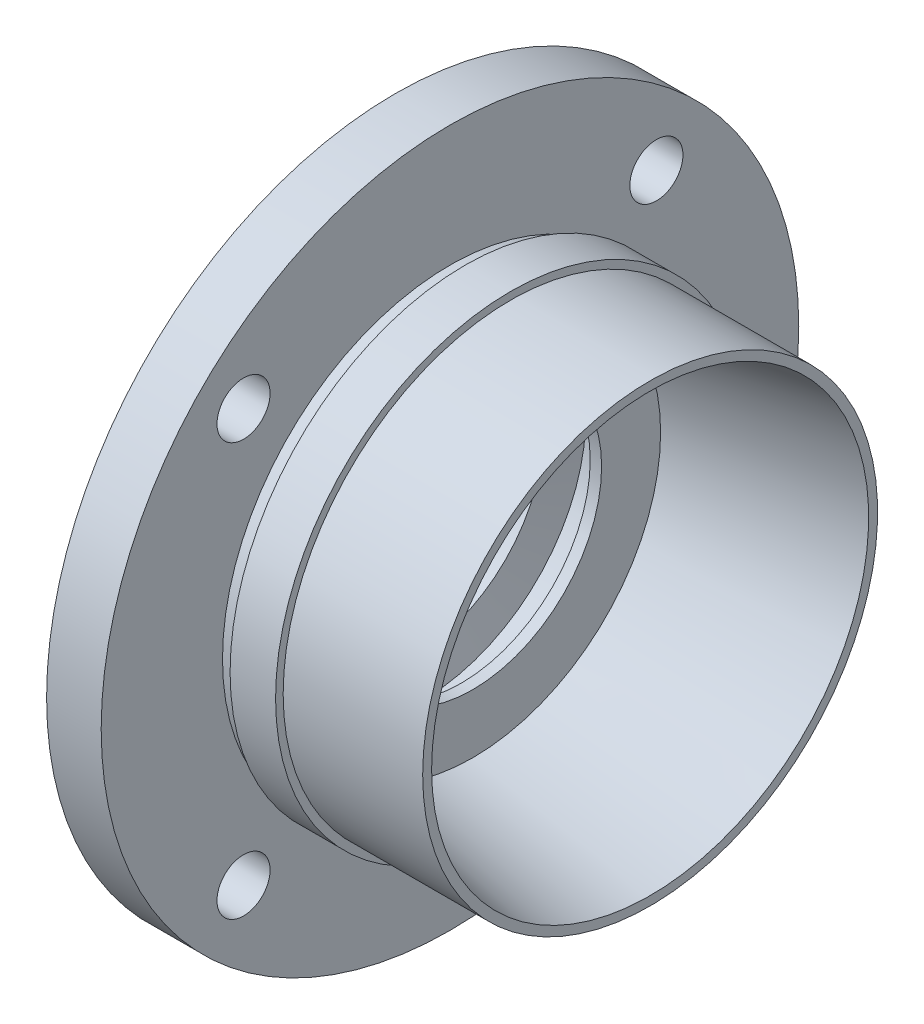
SolidWorks part; units mm, degrees
ref_plane "前视基准面" through (0, 0, 0) normal (0, 0, 1) x (1, 0, 0)
ref_plane "上视基准面" through (0, 0, 0) normal (0, 1, 0) x (1, 0, 0)
ref_plane "右视基准面" through (0, 0, 0) normal (1, 0, 0) x (0, 0, -1)
sketch "草图1" plane through (0, 0, 0) normal (0, 0, 1) x (1, 0, 0)
  line L0 (1, 30) -> (1, 17)
  line L1 (0, 30) -> (0, 46)
  line L2 (10.2, 0) -> (33.6, 0)
  line L3 (1, 30) -> (0, 30)
  line L5 (0, 46) -> (7.2, 46)
  line L6 (7.2, 46) -> (7.2, 30)
  line L7 (7.2, 30) -> (9.2, 30)
  line L8 (9.2, 30) -> (9.2, 31)
  line L9 (9.2, 31) -> (15.2, 31)
  line L10 (15.2, 31) -> (15.2, 30)
  line L11 (15.2, 30) -> (33.6, 30)
  line L13 (1, 17) -> (2.5, 17)
  line L14 (8.7, 17) -> (10.2, 17)
  line L15 (10.2, 17) -> (10.2, 24.78)
  line L16 (33.6, 30) -> (33.6, 28.8226)
  line L17 (10.2, 24.78) -> (33.6, 28.8226)
  line L18 (3.6, 21.5) -> (7.6, 21.5)
  line L19 (7.6, 21.5) -> (8.7, 17)
  line L20 (3.6, 21.5) -> (2.5, 17)
  line L21 (0, 0) -> (10.2, 0)
revolve "旋转1" add sketch "草图1" angle 360 about L21
sketch "草图2" plane through (0, 0, 0) normal (-1, 0, 0) x (0, 0, 1)
  circle A1 centre (-27.2236, 27.2236) radius 3.5
  circle A2 centre (27.2236, 27.2236) radius 3.5
  circle A3 centre (-27.2236, -27.2236) radius 3.5
  circle A4 centre (27.2236, -27.2236) radius 3.5
extrude "切除-拉伸1" cut sketch "草图2" against normal through all
